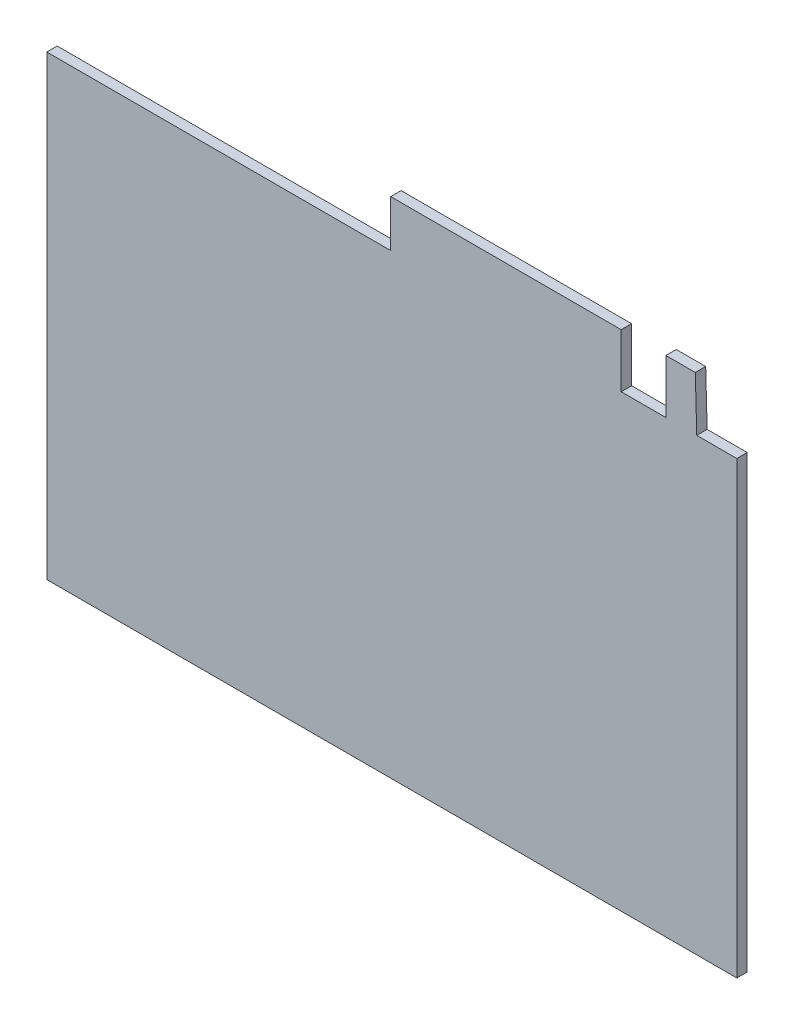
SolidWorks part; units mm, degrees
material "ABS"
ref_plane "Front Plane" through (0, 0, 0) normal (0, 0, 1) x (1, 0, 0)
ref_plane "Top Plane" through (0, 0, 0) normal (0, 1, 0) x (1, 0, 0)
ref_plane "Right Plane" through (0, 0, 0) normal (1, 0, 0) x (0, 0, -1)
sketch "Sketch1" plane through (0, 0, 0) normal (0, 0, 1) x (1, 0, 0)
  line L0 (28.5714, 236.0602) -> (28.5714, 237.0518)
  line L1 (28.5714, 277.1048) -> (28.5714, -22.8952) construction
  line L2 (28.5714, 237.0518) -> (5.4155, 237.0518)
  line L3 (5.4155, 237.0518) -> (4.5714, 268.1048)
  line L4 (4.5714, 268.1048) -> (-12.4286, 268.1048)
  line L5 (-12.4286, 268.1048) -> (-12.4286, 237.0518)
  line L6 (-12.4286, 237.0518) -> (-38.2166, 237.0518)
  line L7 (-38.2166, 237.0518) -> (-38.2166, 268.1048)
  line L8 (-221.4286, 268.1048) -> (28.5714, 268.1048) construction
  line L9 (-38.2166, 268.1048) -> (-171.4286, 268.1048)
  line L10 (-171.4286, 268.1048) -> (-171.4286, 241.1048)
  line L11 (-171.4286, 241.1048) -> (-370.1235, 241.1048)
  line L12 (-370.1235, 241.1048) -> (-370.1235, -22.8952)
  line L13 (-370.1235, -22.8952) -> (28.5714, -22.8952)
  line L14 (28.5714, -22.8952) -> (28.5714, 236.0602)
extrude "Boss-Extrude1" add sketch "Sketch1" along normal blind 6
